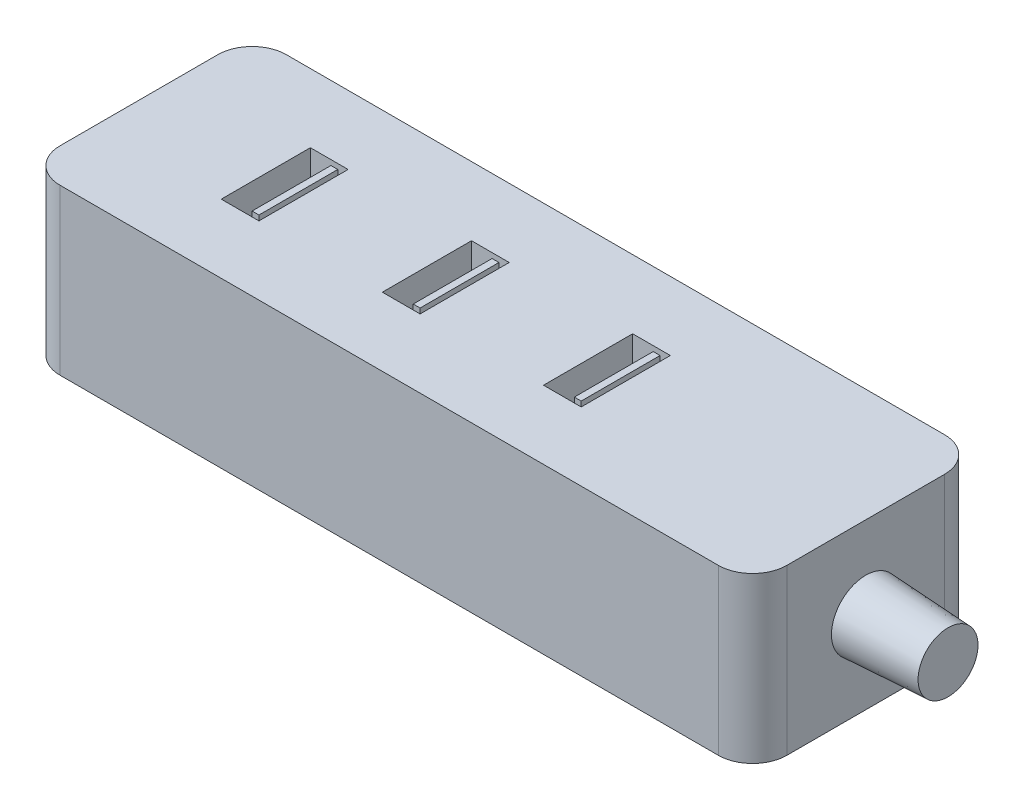
SolidWorks part; units mm, degrees
ref_plane "Front Plane" through (0, 0, 0) normal (0, 0, 1) x (1, 0, 0)
ref_plane "Top Plane" through (0, 0, 0) normal (0, 1, 0) x (1, 0, 0)
ref_plane "Right Plane" through (0, 0, 0) normal (1, 0, 0) x (0, 0, -1)
sketch "Sketch1" plane through (0, 0, 0) normal (0, 1, 0) x (1, 0, 0)
  line L1 (-48, -16.5) -> (48, -16.5)
  line L2 (-53, -11.5) -> (-53, 11.5)
  line L3 (-48, 16.5) -> (48, 16.5)
  line L4 (53, -11.5) -> (53, 11.5)
  line L5 (-53, -16.5) -> (53, 16.5) construction
  line L6 (-53, 16.5) -> (53, -16.5) construction
  arc A0 (-53, 11.5) -> (-48, 16.5) centre (-48, 11.5) cw
  arc A1 (-48, -16.5) -> (-53, -11.5) centre (-48, -11.5) cw
  arc A2 (48, -16.5) -> (53, -11.5) centre (48, -11.5) ccw
  arc A3 (48, 16.5) -> (53, 11.5) centre (48, 11.5) cw
  point P0 (0, 0)
  dimension "D3" = 5
  dimension "D1" = 33
  dimension "D2" = 106
extrude "Boss-Extrude1" add sketch "Sketch1" along normal mid plane 24
sketch "Sketch2" plane through (0, 12, 0) normal (0, 1, 0) x (1, 0, 0)
  line L1 (12.5, -6.5) -> (18, -6.5)
  line L2 (12.5, -6.5) -> (12.5, 6.5)
  line L3 (12.5, 6.5) -> (18, 6.5)
  line L4 (18, -6.5) -> (18, 6.5)
  line L5 (12.5, -6.5) -> (18, 6.5) construction
  line L6 (12.5, 6.5) -> (18, -6.5) construction
  line L7 (-11, -6.5) -> (-5.5, -6.5)
  line L8 (-11, -6.5) -> (-11, 6.5)
  line L9 (-11, 6.5) -> (-5.5, 6.5)
  line L10 (-5.5, -6.5) -> (-5.5, 6.5)
  line L11 (-11, -6.5) -> (-5.5, 6.5) construction
  line L12 (-11, 6.5) -> (-5.5, -6.5) construction
  line L13 (-34.5, -6.5) -> (-29, -6.5)
  line L14 (-34.5, -6.5) -> (-34.5, 6.5)
  line L15 (-34.5, 6.5) -> (-29, 6.5)
  line L16 (-29, -6.5) -> (-29, 6.5)
  line L17 (-34.5, -6.5) -> (-29, 6.5) construction
  line L18 (-34.5, 6.5) -> (-29, -6.5) construction
  line L19 (-53, 11.5) -> (-53, -11.5) construction
  line L22 (16.25, -5.75) -> (17.25, -5.75)
  line L23 (16.25, -5.75) -> (16.25, 5.75)
  line L24 (16.25, 5.75) -> (17.25, 5.75)
  line L25 (17.25, -5.75) -> (17.25, 5.75)
  line L26 (16.25, -5.75) -> (17.25, 5.75) construction
  line L27 (16.25, 5.75) -> (17.25, -5.75) construction
  line L28 (-7.25, -5.75) -> (-6.25, -5.75)
  line L29 (-7.25, -5.75) -> (-7.25, 5.75)
  line L30 (-7.25, 5.75) -> (-6.25, 5.75)
  line L31 (-6.25, -5.75) -> (-6.25, 5.75)
  line L32 (-7.25, -5.75) -> (-6.25, 5.75) construction
  line L33 (-7.25, 5.75) -> (-6.25, -5.75) construction
  line L34 (-29.75, -5.75) -> (-30.75, -5.75)
  line L35 (-29.75, -5.75) -> (-29.75, 5.75)
  line L36 (-29.75, 5.75) -> (-30.75, 5.75)
  line L37 (-30.75, -5.75) -> (-30.75, 5.75)
  line L38 (-29.75, -5.75) -> (-30.75, 5.75) construction
  line L39 (-29.75, 5.75) -> (-30.75, -5.75) construction
  point P0 (15.25, 0)
  point P5 (-8.25, 0)
  point P10 (-31.75, 0)
  point P15 (-6.75, 0)
  point P22 (16.75, 0)
  point P28 (-30.25, 0)
  dimension "D1" = 5.5
  dimension "D2" = 13
  dimension "D3" = 18.5
  dimension "D4" = 18
  dimension "D5" = 18
  dimension "D6" = 0.75
  dimension "D7" = 0.75
  dimension "D8" = 1
  dimension "D9" = 0.75
  dimension "D10" = 0.75
extrude "Cut-Extrude1" cut sketch "Sketch2" against normal blind 10
sketch "Sketch3" plane through (-53, 0, 0) normal (-1, 0, 0) x (0, 0, 1)
  line L1 (-7.7, -3.75) -> (7.7, -3.75)
  line L2 (-7.7, -3.75) -> (-7.7, 3.75)
  line L3 (-7.7, 3.75) -> (7.7, 3.75)
  line L4 (7.7, -3.75) -> (7.7, 3.75)
  line L5 (-7.7, -3.75) -> (7.7, 3.75) construction
  line L6 (-7.7, 3.75) -> (7.7, -3.75) construction
  line L7 (-6.45, 1.5) -> (6.45, 1.5)
  line L8 (-6.45, 1.5) -> (-6.45, 2.5)
  line L9 (-6.45, 2.5) -> (6.45, 2.5)
  line L10 (6.45, 1.5) -> (6.45, 2.5)
  line L11 (-6.45, 1.5) -> (6.45, 2.5) construction
  line L12 (-6.45, 2.5) -> (6.45, 1.5) construction
  point P0 (0, 0)
  point P6 (0, 2)
  dimension "D1" = 7.5
  dimension "D2" = 15.4
  dimension "D3" = 1.25
  dimension "D4" = 1
  dimension "D5" = 1.25
extrude "Cut-Extrude2" cut sketch "Sketch3" against normal blind 10
sketch "Sketch4" plane through (53, 0, 0) normal (1, 0, 0) x (0, 0, -1)
  circle A0 centre (0, 0) radius 5
  dimension "D1" = 10
extrude "Boss-Extrude2" add sketch "Sketch4" along normal blind 12 draft 3
